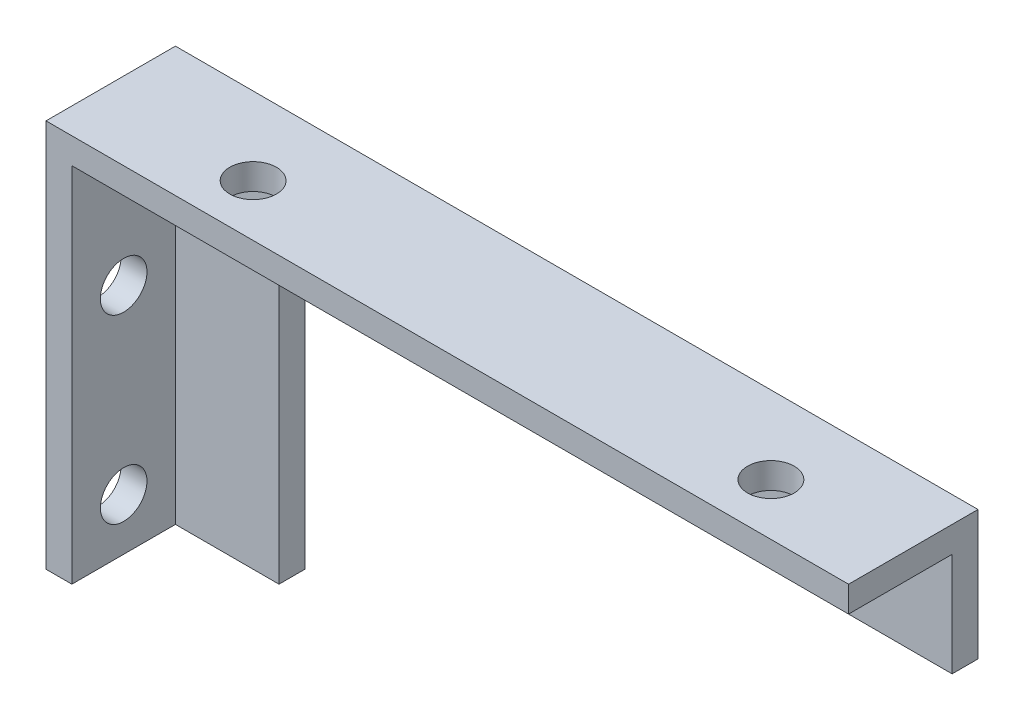
SolidWorks part; units mm, degrees
ref_plane "Plan de face" through (0, 0, 0) normal (0, 0, 1) x (1, 0, 0)
ref_plane "Plan de dessus" through (0, 0, 0) normal (0, 1, 0) x (1, 0, 0)
ref_plane "Plan de droite" through (0, 0, 0) normal (1, 0, 0) x (0, 0, -1)
sketch "Esquisse1" plane through (0, 0, 0) normal (0, 0, 1) x (1, 0, 0)
  line L0 (0, 0) -> (31, 0)
  line L1 (31, 0) -> (31, -5)
  line L2 (31, -5) -> (5, -5)
  line L3 (5, -5) -> (5, -15)
  line L4 (5, -15) -> (0, -15)
  line L5 (0, -15) -> (0, 0)
  dimension "D1" = 31
  dimension "D2" = 15
  dimension "D3" = 5
  dimension "D4" = 5
extrude "Boss.-Extru.1" add sketch "Esquisse1" along normal blind 5
sketch "Esquisse2" plane through (0, 0, 5) normal (0, 0, 1) x (1, 0, 0)
  line L0 (5, -15) -> (5, -5)
  line L1 (5, -5) -> (31, -5)
  line L2 (31, -5) -> (31, 0)
  line L5 (1, -1) -> (1, -15)
  line L7 (1, -15) -> (5, -15)
  line L8 (0, 0) -> (0, -15) construction
  line L9 (1, -1) -> (31, -1)
  line M9 (0, -15) -> (5, -15)
  line M10 (5, -15) -> (5, -5)
  line M11 (5, -5) -> (31, -5)
  line M12 (31, -5) -> (31, 0)
  dimension "D1" = 1
  dimension "D2" = 1
extrude "Enlèv. mat.-Extru.1" cut sketch "Esquisse2" against normal blind 4 contours L9 L5 M9 M10 M11 M12
sketch "Esquisse3" plane through (1, 0, 0) normal (1, 0, 0) x (0, 0, -1)
  line L0 (-1, -1) -> (-5, -1) construction
  line L2 (-5, -1) -> (-5, -15) construction
  circle A0 centre (-3, -6) radius 0.9
  circle A1 centre (-3, -13) radius 0.9
  point P8 (0, 0)
  dimension "D4" = 1.8
  dimension "D5" = 1.8
  dimension "D1" = 12
  dimension "D2" = 5
  dimension "D3" = 2
sketch "Esquisse4" plane through (0, -1, 0) normal (0, -1, 0) x (1, 0, 0)
  line L0 (1, 1) -> (1, 5) construction
  line L1 (1, 5) -> (31, 5) construction
  circle A0 centre (26, 3) radius 0.9
  circle A1 centre (6, 3) radius 0.9
  point P8 (0, 0)
  dimension "D3" = 1.8
  dimension "D4" = 1.8
  dimension "D1" = 5
  dimension "D2" = 20
  dimension "D5" = 2
extrude "Enlèv. mat.-Extru.2" cut sketch "Esquisse4" against normal blind 10
extrude "Enlèv. mat.-Extru.3" cut sketch "Esquisse3" against normal blind 10
